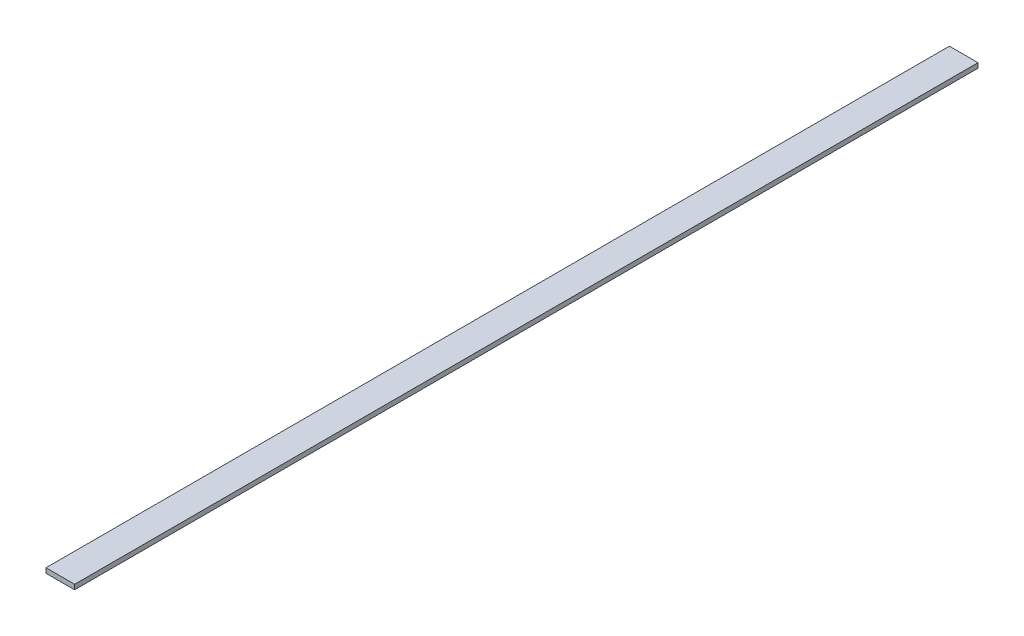
SolidWorks part; units mm, degrees
ref_plane "정면" through (0, 0, 0) normal (0, 0, 1) x (1, 0, 0)
ref_plane "윗면" through (0, 0, 0) normal (0, 1, 0) x (1, 0, 0)
ref_plane "우측면" through (0, 0, 0) normal (1, 0, 0) x (0, 0, -1)
sketch "스케치1" plane through (0, 0, 0) normal (0, 0, 1) x (1, 0, 0)
  line L1 (0, 0) -> (19, 0)
  line L2 (0, 0) -> (0, 3.2)
  line L3 (0, 3.2) -> (19, 3.2)
  line L4 (19, 0) -> (19, 3.2)
  dimension "D1" = 19
  dimension "D2" = 3.2
extrude "보스-돌출1" add sketch "스케치1" along normal blind 600
